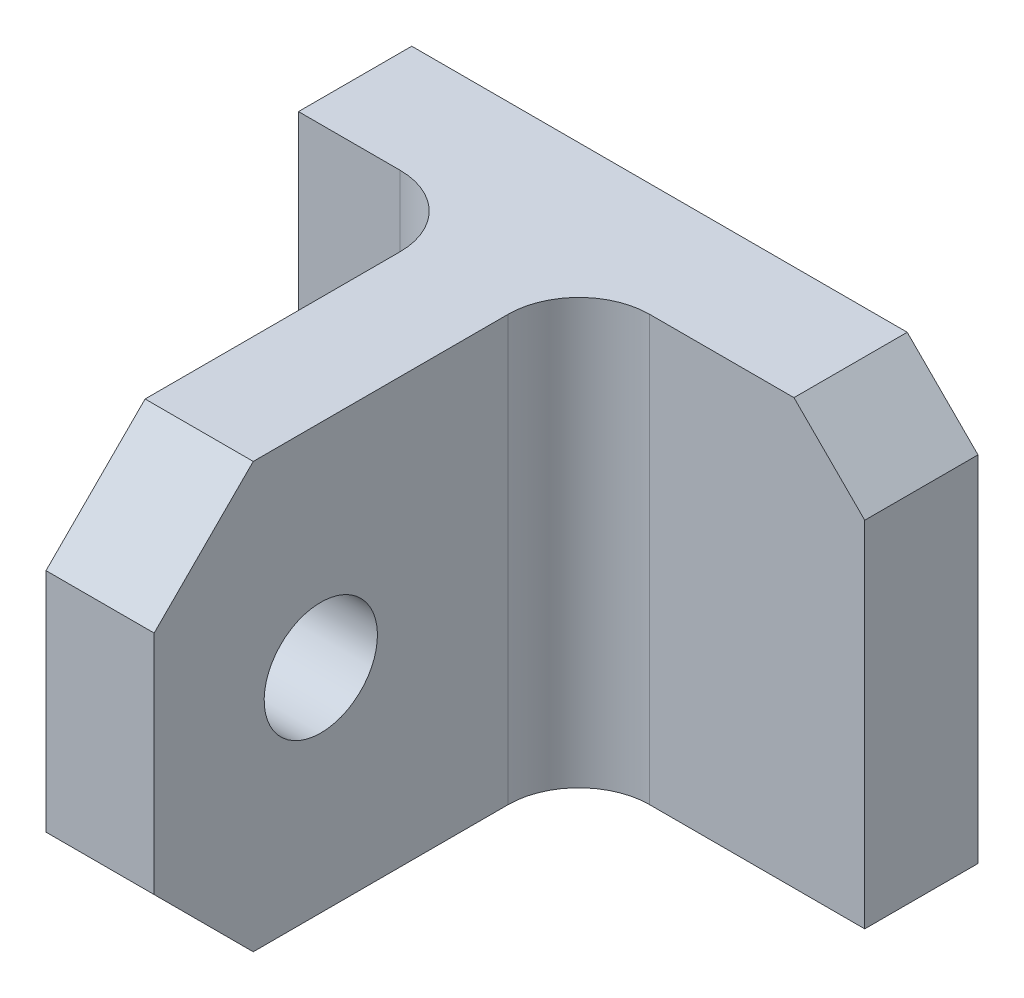
SolidWorks part; units mm, degrees
ref_plane "Спереди" through (0, 0, 0) normal (0, 0, 1) x (1, 0, 0)
ref_plane "Сверху" through (0, 0, 0) normal (0, 1, 0) x (1, 0, 0)
ref_plane "Справа" through (0, 0, 0) normal (1, 0, 0) x (0, 0, -1)
sketch "Эскиз1" plane through (0, 0, 0) normal (0, 0, 1) x (1, 0, 0)
  line L0 (0, 0) -> (-40.4737, 0) construction
  line L1 (-4.0156, 0) -> (3.6244, 0)
  line L2 (-4.0156, 0) -> (-4.0156, -30)
  line L3 (-4.0156, -30) -> (3.6244, -30)
  line L4 (3.6244, 0) -> (3.6244, -30)
  line L5 (-4.0145, 26.644) -> (-4.0145, 27.7899) construction
extrude "Вытянуть1" add sketch "Эскиз1" along normal blind 30
sketch "Эскиз2" plane through (0, 0, 0) normal (0, 0, -1) x (-1, 0, 0)
  line L0 (-3.82, 0) -> (-3.82, 1.4358) construction
  line L2 (-7.64, -15) -> (-13.1315, -15) construction
  line L5 (-23.82, -30) -> (16.18, -30)
  line L6 (-23.82, -30) -> (-23.82, 0)
  line L7 (-23.82, 0) -> (16.18, 0)
  line L8 (16.18, -30) -> (16.18, 0)
extrude "Вытянуть2" add sketch "Эскиз2" along normal blind 8
fillet "Скругление1" radius 5 2 edges
chamfer "Фаска1" distance 7 angle 45 2 edges at (-0.1956, -30, 30) (-0.1956, 0, 30)
sketch "Эскиз3" plane through (-4.0156, 0, 0) normal (-1, 0, 0) x (0, 0, 1)
  circle A0 centre (18.2288, -15) radius 4
extrude "Вырез-Вытянуть1" cut sketch "Эскиз3" against normal through all
chamfer "Фаска2" distance 5 angle 45 1 edges at (23.82, 0, -4)
